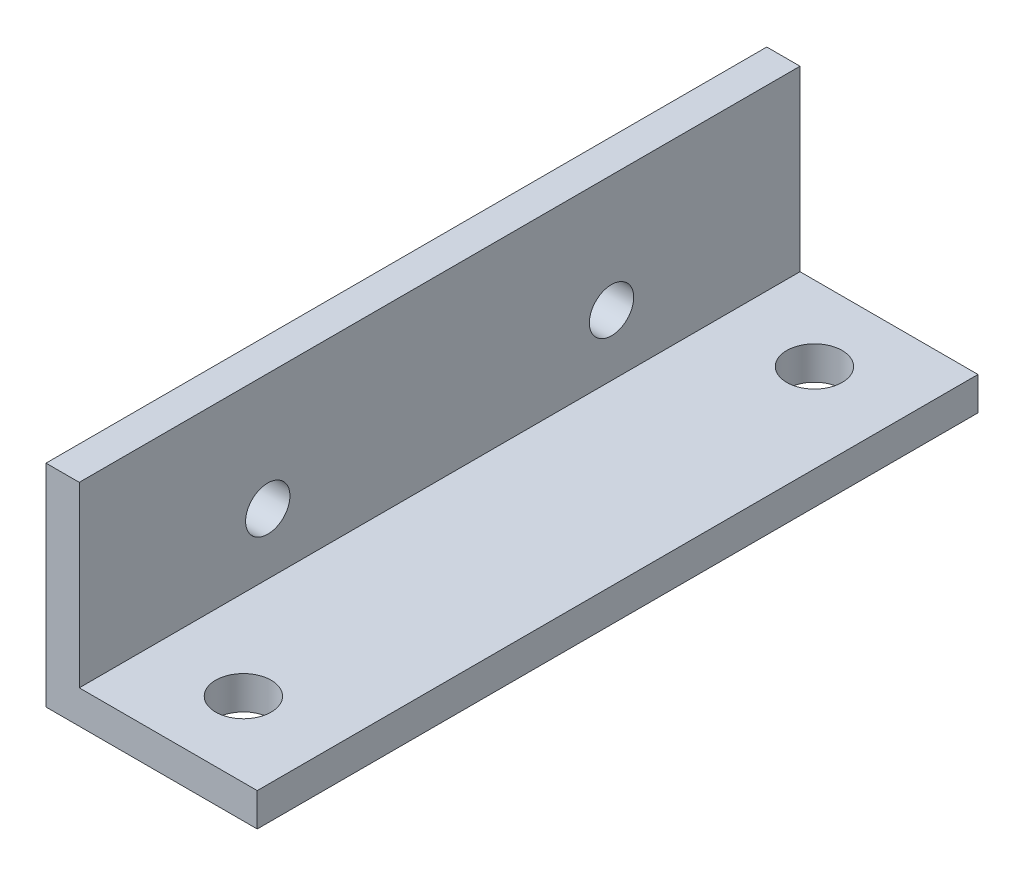
SolidWorks part; units mm, degrees
material "6061-T4 (SS)"
ref_plane "Front Plane" through (0, 0, 0) normal (0, 0, 1) x (1, 0, 0)
ref_plane "Top Plane" through (0, 0, 0) normal (0, 1, 0) x (1, 0, 0)
ref_plane "Right Plane" through (0, 0, 0) normal (1, 0, 0) x (0, 0, -1)
sketch "Sketch1" plane through (0, 0, 0) normal (0, 0, 1) x (1, 0, 0)
  line L0 (0, 0) -> (0, 19.05)
  line L2 (19.05, 0) -> (0, 0)
  dimension "D1" = 19.05
  dimension "D2" = 19.05
extrude "Extrude-Thin1" add sketch "Sketch1" along normal mid plane 65 thin
sketch "Sketch4" plane through (0, 0, 0) normal (-1, 0, 0) x (0, 0, 1)
  line L0 (0, 0) -> (0, 19.05) construction
  line L1 (32.5, 19.05) -> (-32.5, 19.05) construction
  line L2 (-15.5, 8.5) -> (15.5, 8.5) construction
  line L3 (32.5, 0) -> (-32.5, 0) construction
  circle A0 centre (-15.5, 8.5) radius 2
  circle A1 centre (15.5, 8.5) radius 2
  dimension "D1" = 31
  dimension "D2" = 4
  dimension "D3" = 8.5
extrude "Cut-Extrude2" cut sketch "Sketch4" against normal up to next
sketch "Sketch3" plane through (0, 0, 0) normal (0, -1, 0) x (1, 0, 0)
  line L0 (11.05, 25.75) -> (11.05, -25.75) construction
  line L3 (0, 0) -> (19.05, 0) construction
  line L5 (19.05, 32.5) -> (19.05, -32.5) construction
  circle A3 centre (11.05, -25.75) radius 2.5
  circle A5 centre (11.05, 25.75) radius 2.5
  point P1 (10.3315, 25.9249)
  point P2 (10.3146, -26.1631)
  dimension "D1" = 51.5
  dimension "D2" = 8
  dimension "D3" = 5
extrude "Cut-Extrude1" cut sketch "Sketch3" against normal up to surface (3 mm away) up to face at (11.025, 3, 0)
